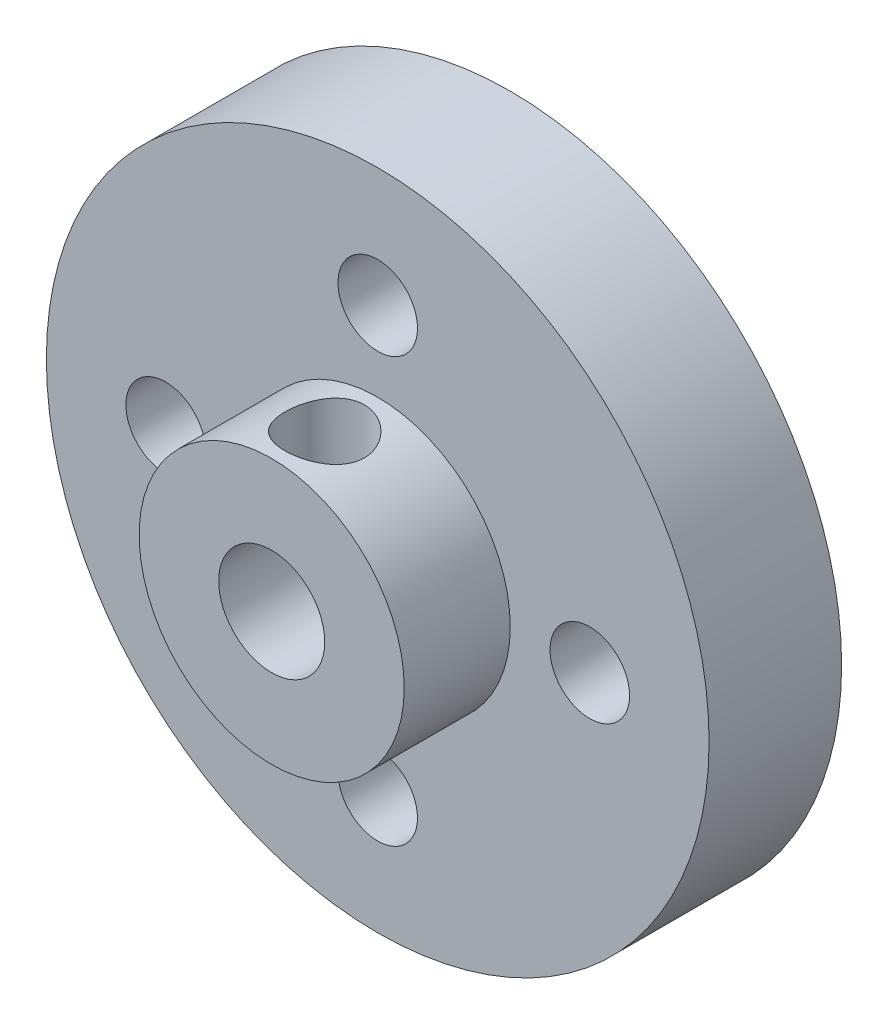
SolidWorks part; units mm, degrees
material "Alliage 1060"
ref_plane "Plan de face" through (0, 0, 0) normal (0, 0, 1) x (1, 0, 0)
ref_plane "Plan de dessus" through (0, 0, 0) normal (0, 1, 0) x (1, 0, 0)
ref_plane "Plan de droite" through (0, 0, 0) normal (1, 0, 0) x (0, 0, -1)
sketch "Esquisse1" plane through (0, 0, 0) normal (0, 0, 1) x (1, 0, 0)
  circle A0 centre (0, 0) radius 12.5
  circle A1 centre (0, 0) radius 5
  circle A2 centre (0, 8) radius 1.5
  circle A3 centre (8, 0) radius 1.5
  circle A4 centre (0, -8) radius 1.5
  circle A5 centre (-8, 0) radius 1.5
  point P15 (0, 0)
  dimension "D1" = 25
  dimension "D2" = 10
  dimension "D3" = 3
  dimension "D4" = 8
  dimension "D5" = 4
extrude "Boss.-Extru.1" add sketch "Esquisse1" along normal blind 5
sketch "Esquisse2" plane through (0, 0, 5) normal (0, 0, 1) x (1, 0, 0)
  circle A0 centre (0, 0) radius 5 construction
  circle A1 centre (0, 0) radius 5
extrude "Boss.-Extru.2" add sketch "Esquisse2" along normal blind 4 separate body
sketch "Esquisse3" plane through (0, 0, 0) normal (0, 1, 0) x (1, 0, 0)
  line L0 (5, -9) -> (5, -5) construction
  line L1 (5, -9) -> (5, -5)
  circle A0 centre (0, -7) radius 1.5
  point P6 (5, -7)
  dimension "D1" = 3
sketch "Esquisse4" plane through (0, 0, 9) normal (0, 0, 1) x (1, 0, 0)
  circle A0 centre (0, 0) radius 2
  dimension "D1" = 4
extrude "Enlèv. mat.-Extru.1" cut sketch "Esquisse4" against normal through all
extrude "Enlèv. mat.-Extru.2" cut sketch "Esquisse3" along normal through all contours A0
